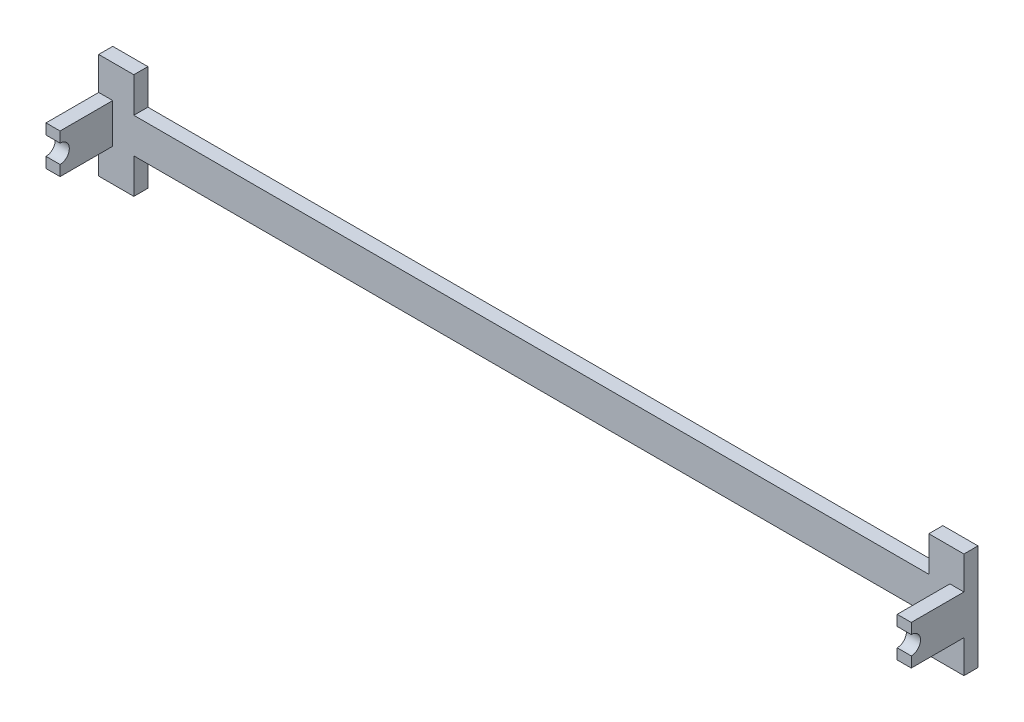
SolidWorks part; units mm, degrees
ref_plane "前视基准面" through (0, 0, 0) normal (0, 0, 1) x (1, 0, 0)
ref_plane "上视基准面" through (0, 0, 0) normal (0, 1, 0) x (1, 0, 0)
ref_plane "右视基准面" through (0, 0, 0) normal (1, 0, 0) x (0, 0, -1)
other "Configuration Table"
sketch "草图1" plane through (0, 0, 0) normal (0, 0, 1) x (1, 0, 0)
  line L0 (-14, 0) -> (-12.6056, 0) construction
  line L1 (-14, 5) -> (232.3, 5)
  line L2 (-14, 5) -> (-14, -5)
  line L3 (-14, -5) -> (232.3, -5)
  line L4 (232.3, 5) -> (232.3, -5)
  line L6 (0, -3.75) -> (0, 3.75) construction
  line L8 (225, -3.75) -> (225, 3.75) construction
  dimension "D1" = 10
  dimension "D2" = 7.3
  dimension "D3" = 14
extrude "凸台-拉伸1" add sketch "草图1" against normal blind 4 from offset 15 offset against normal yes
sketch "草图2" plane through (0, 0, -19) normal (0, 0, -1) x (-1, 0, 0)
  line L0 (14, 5) -> (14, -5) construction
  line L1 (14, 15) -> (4, 15)
  line L2 (14, 15) -> (14, -15)
  line L3 (14, -15) -> (4, -15)
  line L4 (4, 15) -> (4, -15)
  line L5 (14, 0) -> (4, 0) construction
  line L6 (-232.3, 0) -> (-222.3, 0) construction
  line L7 (-232.3, -15) -> (-222.3, -15)
  line L8 (-232.3, -15) -> (-232.3, 15)
  line L9 (-232.3, 15) -> (-222.3, 15)
  line L10 (-222.3, -15) -> (-222.3, 15)
  line L11 (-232.3, -5) -> (-232.3, 5) construction
  dimension "D1" = 30
  dimension "D2" = 10
  dimension "D3" = 30
  dimension "D4" = 10
extrude "凸台-拉伸2" add sketch "草图2" against normal blind 4
sketch "草图4" plane through (232.3, 0, 0) normal (1, 0, 0) x (0, 0, -1)
  line L0 (0, -2.63) -> (0, -5.63)
  line L1 (0, 2.63) -> (0, 5.63)
  line L2 (0, 5.63) -> (15, 5.63)
  line L3 (15, -15) -> (15, 15) construction
  line L4 (15, 5.63) -> (15, -5.63)
  line L5 (15, -5.63) -> (0, -5.63)
  arc A0 (-1.8597, -1.8597) -> (-1.8597, 1.8597) centre (0, 0) ccw construction
  arc A1 (0, -2.63) -> (0, 2.63) centre (0, 0) ccw
  dimension "D1" = 3
  dimension "D2" = 3
extrude "凸台-拉伸3" add sketch "草图4" against normal blind 4
sketch "草图5" plane through (-14, 0, 0) normal (-1, 0, 0) x (0, 0, 1)
  line L5 (0, 2.63) -> (0, 5.63)
  line L6 (0, 5.63) -> (-15, 5.63)
  line L7 (-15, 5.63) -> (-15, -5.63)
  line L8 (-15, -5.63) -> (0, -5.63)
  line L9 (0, -5.63) -> (0, -2.63)
  line L10 (0, 2.63) -> (0, 5.63)
  line L11 (0, 5.63) -> (-15, 5.63)
  line L12 (-15, 5.63) -> (-15, -5.63)
  line L13 (-15, -5.63) -> (0, -5.63)
  line L14 (0, -5.63) -> (0, -2.63)
  arc A1 (0, 2.63) -> (0, -2.63) centre (0, 0) ccw
  arc A2 (0, 2.63) -> (0, -2.63) centre (0, 0) ccw
  dimension "D1" = 0
extrude "凸台-拉伸4" add sketch "草图5" against normal blind 4
